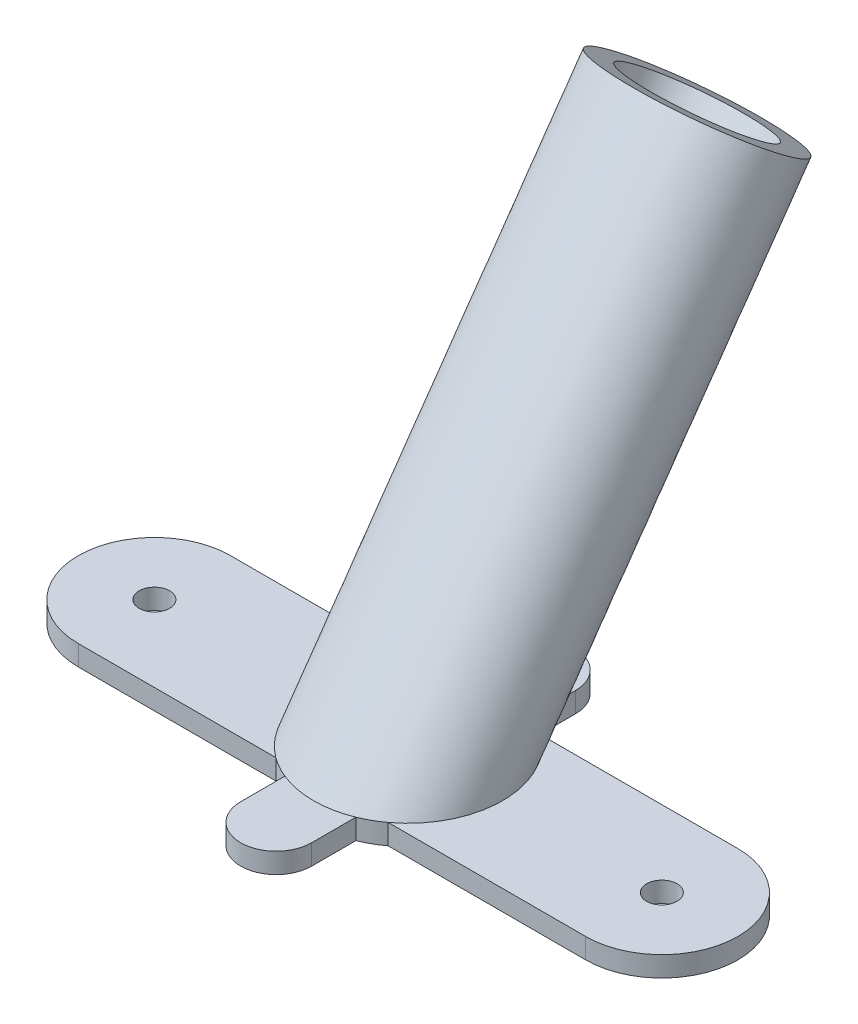
SolidWorks part; units mm, degrees
ref_plane "Alzado" through (0, 0, 0) normal (0, 0, 1) x (1, 0, 0)
ref_plane "Planta" through (0, 0, 0) normal (0, 1, 0) x (1, 0, 0)
ref_plane "Vista lateral" through (0, 0, 0) normal (1, 0, 0) x (0, 0, -1)
sketch "Croquis1" plane through (0, 0, 0) normal (0, 1, 0) x (1, 0, 0)
  circle A2 centre (0, 0) radius 9.325
  circle A4 centre (0, 0) radius 6.835
sketch "Croquis6" plane through (0, 0, 0) normal (1, 0, 0) x (0, 0, -1)
  line L0 (9.3454, 0) -> (40.8921, 45.0534)
sweep "Barrer1" add profiles "Croquis1" path "Croquis6"
sketch "Croquis11" plane through (0, 0, 0) normal (0, -1, 0) x (1, 0, 0)
  line L0 (0, 0) -> (3.5, 0)
  line L1 (0, 0) -> (3.5, 0) construction
  line L2 (-25, 7.5) -> (-5.5413, 7.5)
  line L3 (-25, -7.5) -> (-5.5413, -7.5)
  line L5 (-3.5, 8.6432) -> (-3.5, 13)
  line L6 (-3.5, -13) -> (-3.5, -8.6432)
  line L7 (3.5, -13) -> (3.5, -8.6432)
  line L8 (5.5413, 7.5) -> (25, 7.5)
  line L9 (3.5, 8.6432) -> (3.5, 13)
  line L12 (5.5413, -7.5) -> (25, -7.5)
  arc A0 (-25, 7.5) -> (-25, -7.5) centre (-25, 0) ccw
  arc A1 (25, -7.5) -> (25, 7.5) centre (25, 0) ccw
  arc A2 (-3.5, -13) -> (3.5, -13) centre (0, -13) ccw
  arc A3 (3.5, 13) -> (-3.5, 13) centre (0, 13) ccw
  arc A4 (-5.5413, -7.5) -> (-3.5, -8.6432) centre (0, 0) ccw
  arc A5 (-3.5, 8.6432) -> (-5.5413, 7.5) centre (0, 0) ccw
  arc A6 (5.5413, 7.5) -> (3.5, 8.6432) centre (0, 0) ccw
  arc A7 (3.5, -8.6432) -> (5.5413, -7.5) centre (0, 0) ccw
  circle A8 centre (-25, 0) radius 1.5
  circle A9 centre (25, 0) radius 1.5
  point P4 (0, 0)
  point P13 (0, 0)
extrude "Saliente-Extruir1" add sketch "Croquis11" along normal blind 2
sketch "Croquis12" plane through (0, 0, 0) normal (1, 0, 0) x (0, 0, -1)
  line L0 (22.2217, 45.0534) -> (40.8717, 45.0534)
  line L1 (22.2217, 45.0534) -> (40.8717, 45.0534)
  line L2 (22.2217, 45.0534) -> (40.8717, 20.2409)
  line L3 (40.8717, 20.2409) -> (40.8717, 45.0534)
sketch "Croquis13" plane through (0, 0, 0) normal (1, 0, 0) x (0, 0, -1)
  line L0 (22.2217, 45.0534) -> (40.8717, 31.9945)
  line L2 (22.2217, 45.0534) -> (40.8717, 45.0534)
  line L3 (40.8717, 45.0534) -> (40.8717, 31.9945)
  line L4 (40.8717, 20.2409) -> (40.8717, 45.0534) construction
extrude "Cortar-Extruir2" cut sketch "Croquis13" against normal through all and the other way through all
